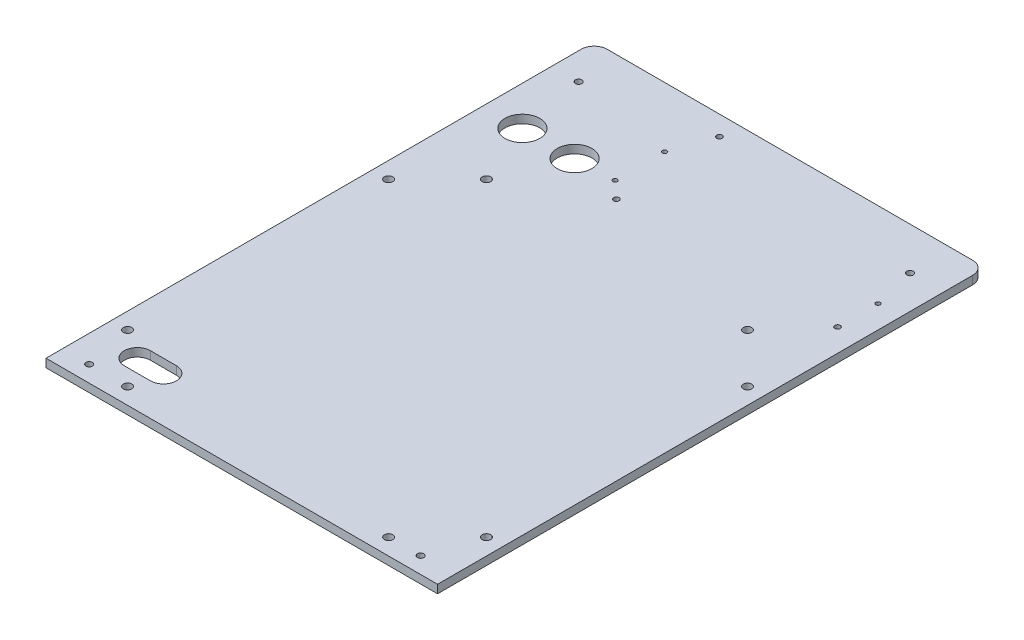
SolidWorks part; units mm, degrees
material "6061 Alloy"
ref_plane "Front Plane" through (0, 0, 0) normal (0, 0, 1) x (1, 0, 0)
ref_plane "Top Plane" through (0, 0, 0) normal (0, 1, 0) x (1, 0, 0)
ref_plane "Right Plane" through (0, 0, 0) normal (1, 0, 0) x (0, 0, -1)
sketch "Sketch1" plane through (0, 0, 0) normal (0, 1, 0) x (1, 0, 0)
  line L1 (0, 0) -> (300, 0)
  line L2 (0, 0) -> (0, 420)
  line L3 (0, 420) -> (300, 420)
  line L4 (300, 0) -> (300, 420)
  dimension "D1" = 300
  dimension "D2" = 420
extrude "Boss-Extrude1" add sketch "Sketch1" along normal blind 6.35
sketch "Sketch3" plane through (0, 6.35, 0) normal (0, 1, 0) x (1, 0, 0)
  line L0 (0, 0) -> (300, 0) construction
  line L1 (150, 0) -> (150, 12.5) construction
  line L2 (50, 12.5) -> (250, 12.5) construction
  line L3 (0, 420) -> (0, 0) construction
  line L4 (0, 150) -> (12.5, 150) construction
  line L5 (12.5, 50) -> (12.5, 250) construction
  circle A0 centre (50, 12.5) radius 3.25
  circle A1 centre (250, 12.5) radius 3.25
  circle A2 centre (12.5, 50) radius 3.25
  circle A3 centre (12.5, 250) radius 3.25
  circle A4 centre (250, 287.5) radius 3.25
  circle A5 centre (50, 287.5) radius 3.25
  circle A6 centre (287.5, 250) radius 3.25
  circle A7 centre (287.5, 50) radius 3.25
  point P6 (150, 12.5)
  point P13 (12.5, 150)
  dimension "D5" = 6.5
  dimension "D1" = 200
  dimension "D2" = 12.5
  dimension "D3" = 50
  dimension "D4" = 50
extrude "Cut-Extrude1" cut sketch "Sketch3" against normal through all
sketch "Sketch4" plane through (0, 6.35, 0) normal (0, 1, 0) x (1, 0, 0)
  line L0 (0, 12.5) -> (20.55, 12.5) construction
  line L1 (0, 420) -> (0, 0) construction
  line L2 (0, 0) -> (300, 0) construction
  line L3 (300, 12.5) -> (274.55, 12.5) construction
  line L4 (300, 0) -> (300, 420) construction
  line L5 (20.55, 12.5) -> (20.55, 387.5) construction
  line L6 (274.55, 12.5) -> (274.55, 387.5) construction
  circle A0 centre (20.55, 12.5) radius 2.5
  circle A1 centre (274.55, 12.5) radius 2.5
  circle A2 centre (20.55, 387.5) radius 2.5
  circle A3 centre (274.55, 387.5) radius 2.5
  dimension "D2" = 5
  dimension "D1" = 20.55
  dimension "D3" = 12.5
  dimension "D4" = 12.5
  dimension "D5" = 25.45
  dimension "D6" = 375
extrude "Cut-Extrude2" cut sketch "Sketch4" against normal through all
sketch "Sketch6" plane through (0, 6.35, 0) normal (0, 1, 0) x (1, 0, 0)
  line L0 (300, 355) -> (282.5, 355) construction
  line L2 (300, 0) -> (300, 420) construction
  line L4 (282.5, 355) -> (282.5, 420) construction
  line L5 (300, 420) -> (0, 420) construction
  line L6 (100, 420) -> (100, 374) construction
  line L7 (0, 374) -> (100, 374) construction
  line L8 (0, 420) -> (0, 0) construction
  line L9 (100, 374) -> (100, 336) construction
  circle A0 centre (282.5, 355) radius 1.7
  circle A1 centre (100, 336) radius 1.7
  circle A2 centre (100, 374) radius 1.7
  dimension "D3" = 3.4
  dimension "D1" = 17.5
  dimension "D2" = 65
  dimension "D4" = 100
  dimension "D5" = 46
  dimension "D6" = 38
extrude "Cut-Extrude3" cut sketch "Sketch6" against normal through all
ref_plane "Plane1" through (150, 0, 0) normal (1, 0, 0) x (0, 0, -1)
sketch "Sketch7" plane through (0, 6.35, 0) normal (0, 1, 0) x (1, 0, 0)
  line L0 (300, 0) -> (300, 420) construction
  line L1 (290, 420) -> (290, 410) construction
  line L2 (290, 410) -> (300, 410) construction
  line L3 (300, 420) -> (0, 420) construction
  line L4 (290, 420) -> (300, 420)
  line L5 (300, 420) -> (300, 410)
  line L6 (150, -3.4925) -> (150, 3.4925) construction
  line L7 (10, 420) -> (0, 420)
  line L8 (0, 420) -> (0, 410)
  arc A0 (300, 410) -> (290, 420) centre (290, 410) ccw
  arc A1 (0, 410) -> (10, 420) centre (10, 410) cw
  dimension "D1" = 10
extrude "Cut-Extrude4" cut sketch "Sketch7" against normal blind 10
sketch "Sketch8" plane through (0, 6.35, 0) normal (0, 1, 0) x (1, 0, 0)
  line L0 (0, 410) -> (0, 0) construction
  line L1 (290, 420) -> (10, 420) construction
  circle A0 centre (70, 335) radius 13.335
  circle A1 centre (30, 335) radius 13.335
  dimension "D1" = 26.67
  dimension "D2" = 70
  dimension "D3" = 40
  dimension "D4" = 85
extrude "Cut-Extrude5" cut sketch "Sketch8" against normal through all
sketch "Sketch9" plane through (0, 6.35, 0) normal (0, 1, 0) x (1, 0, 0)
  line L0 (290, 420) -> (10, 420) construction
  circle A0 centre (282.5, 324) radius 2.1
  circle A1 centre (111, 405) radius 2.1
  circle A2 centre (113, 324) radius 2.1
  dimension "D1" = 4.2
  dimension "D2" = 2
  dimension "D3" = 169.5
  dimension "D4" = 81
  dimension "D5" = 15
extrude "Cut-Extrude6" cut sketch "Sketch9" against normal through all
sketch "Sketch10" plane through (0, 6.35, 0) normal (0, 1, 0) x (1, 0, 0)
  line L0 (55, 35) -> (35, 35) construction
  line L1 (55, 25) -> (35, 25)
  line L2 (55, 45) -> (35, 45)
  line L4 (45, 25) -> (45, 0) construction
  line L5 (0, 0) -> (300, 0) construction
  line L6 (0, 410) -> (0, 0) construction
  arc A0 (55, 25) -> (55, 45) centre (55, 35) ccw
  arc A1 (35, 45) -> (35, 25) centre (35, 35) ccw
  point P2 (45, 35)
  dimension "D4" = 35
  dimension "D1" = 20
  dimension "D2" = 20
  dimension "D3" = 25
extrude "Cut-Extrude7" cut sketch "Sketch10" against normal through all
